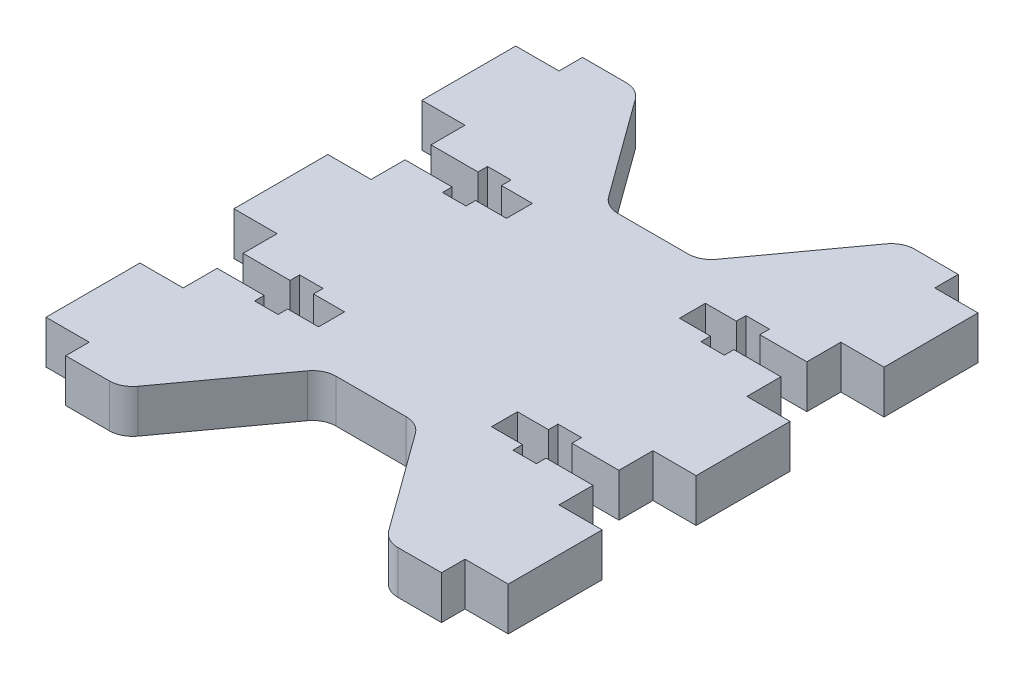
SolidWorks part; units mm, degrees
ref_plane "Front Plane" through (0, 0, 0) normal (0, 0, 1) x (1, 0, 0)
ref_plane "Top Plane" through (0, 0, 0) normal (0, 1, 0) x (1, 0, 0)
ref_plane "Right Plane" through (0, 0, 0) normal (1, 0, 0) x (0, 0, -1)
sketch "Sketch1" plane through (0, 0, 0) normal (0, 1, 0) x (1, 0, 0)
  line L0 (0, 34.925) -> (0, -34.925) construction
  line L1 (25.4, -34.925) -> (17.8955, -34.925)
  line L2 (25.4, -34.925) -> (25.4, -31.75)
  line L3 (25.4, 34.925) -> (17.8955, 34.925)
  line L4 (-25.4, -34.925) -> (-25.4, -31.75)
  line L5 (25.4, -34.925) -> (-25.4, 34.925) construction
  line L6 (25.4, 34.925) -> (-25.4, -34.925) construction
  line L7 (-31.242, 19.05) -> (-25.4, 19.05)
  line L8 (-31.242, 19.05) -> (-31.242, 31.75)
  line L9 (-31.242, 31.75) -> (-25.4, 31.75)
  line L10 (-25.4, 6.35) -> (-25.4, 10.9474)
  line L11 (-31.242, 19.05) -> (-25.4, 31.75) construction
  line L12 (-31.242, 31.75) -> (-25.4, 19.05) construction
  line L13 (-31.242, -6.35) -> (-25.4, -6.35)
  line L14 (-31.242, -6.35) -> (-31.242, 6.35)
  line L15 (-31.242, 6.35) -> (-25.4, 6.35)
  line L16 (-25.4, -19.05) -> (-25.4, -14.4526)
  line L17 (-31.242, -6.35) -> (-25.4, 6.35) construction
  line L18 (-31.242, 6.35) -> (-25.4, -6.35) construction
  line L19 (-31.242, -31.75) -> (-25.4, -31.75)
  line L20 (-31.242, -31.75) -> (-31.242, -19.05)
  line L21 (-31.242, -19.05) -> (-25.4, -19.05)
  line L22 (-25.4, 12.7) -> (25.4, 12.7) construction
  line L23 (-31.242, -31.75) -> (-25.4, -19.05) construction
  line L24 (-31.242, -19.05) -> (-25.4, -31.75) construction
  line L25 (-25.4, 31.75) -> (-25.4, 34.925)
  line L26 (-25.4, 0) -> (25.4, 0) construction
  line L27 (-19.05, 14.4526) -> (-19.05, 15.748)
  line L28 (-19.05, 10.9474) -> (-25.4, 10.9474)
  line L29 (-15.875, 14.4526) -> (-15.875, 15.748)
  line L30 (-19.05, 14.4526) -> (-25.4, 14.4526)
  line L31 (-11.692, -14.4526) -> (-15.875, -10.9474) construction
  line L32 (-19.05, 10.9474) -> (-25.4, 14.4526) construction
  line L33 (-19.05, 14.4526) -> (-25.4, 10.9474) construction
  line L34 (-15.875, 9.652) -> (-19.05, 9.652)
  line L35 (-15.875, 9.652) -> (-15.875, 10.9474)
  line L36 (-15.875, 15.748) -> (-19.05, 15.748)
  line L37 (-19.05, 9.652) -> (-19.05, 10.9474)
  line L38 (-15.875, 9.652) -> (-19.05, 15.748) construction
  line L39 (-15.875, 15.748) -> (-19.05, 9.652) construction
  line L40 (-11.692, 10.9474) -> (-15.875, 10.9474)
  line L41 (-11.692, 10.9474) -> (-11.692, 14.4526)
  line L42 (-11.692, 14.4526) -> (-15.875, 14.4526)
  line L43 (-25.4, 14.4526) -> (-25.4, 19.05)
  line L44 (-11.692, 10.9474) -> (-15.875, 14.4526) construction
  line L45 (-11.692, 14.4526) -> (-15.875, 10.9474) construction
  line L46 (-11.692, -10.9474) -> (-15.875, -14.4526) construction
  line L47 (-15.875, -15.748) -> (-19.05, -9.652) construction
  line L48 (-15.875, -9.652) -> (-19.05, -15.748) construction
  line L49 (-19.05, -14.4526) -> (-25.4, -10.9474) construction
  line L50 (-19.05, -10.9474) -> (-25.4, -14.4526) construction
  line L51 (-11.692, -14.4526) -> (-15.875, -14.4526)
  line L52 (-11.692, -10.9474) -> (-11.692, -14.4526)
  line L53 (-11.692, -10.9474) -> (-15.875, -10.9474)
  line L54 (-19.05, -9.652) -> (-19.05, -10.9474)
  line L55 (-15.875, -15.748) -> (-19.05, -15.748)
  line L56 (-15.875, -9.652) -> (-15.875, -10.9474)
  line L57 (-15.875, -9.652) -> (-19.05, -9.652)
  line L58 (-19.05, -14.4526) -> (-25.4, -14.4526)
  line L59 (-15.875, -14.4526) -> (-15.875, -15.748)
  line L60 (-19.05, -10.9474) -> (-25.4, -10.9474)
  line L61 (-19.05, -14.4526) -> (-19.05, -15.748)
  line L62 (-25.4, -10.9474) -> (-25.4, -6.35)
  line L63 (19.05, -10.9474) -> (25.4, -14.4526) construction
  line L64 (19.05, -14.4526) -> (25.4, -10.9474) construction
  line L65 (15.875, -9.652) -> (19.05, -15.748) construction
  line L66 (15.875, -15.748) -> (19.05, -9.652) construction
  line L67 (11.692, -10.9474) -> (15.875, -14.4526) construction
  line L68 (11.692, 14.4526) -> (15.875, 10.9474) construction
  line L69 (11.692, 10.9474) -> (15.875, 14.4526) construction
  line L70 (15.875, 15.748) -> (19.05, 9.652) construction
  line L71 (15.875, 9.652) -> (19.05, 15.748) construction
  line L72 (19.05, 14.4526) -> (25.4, 10.9474) construction
  line L73 (19.05, 10.9474) -> (25.4, 14.4526) construction
  line L74 (11.692, -14.4526) -> (15.875, -10.9474) construction
  line L75 (31.242, -19.05) -> (25.4, -31.75) construction
  line L76 (31.242, -31.75) -> (25.4, -19.05) construction
  line L77 (31.242, 6.35) -> (25.4, -6.35) construction
  line L78 (31.242, -6.35) -> (25.4, 6.35) construction
  line L79 (31.242, 31.75) -> (25.4, 19.05) construction
  line L80 (31.242, 19.05) -> (25.4, 31.75) construction
  line L81 (25.4, -10.9474) -> (25.4, -6.35)
  line L82 (19.05, -14.4526) -> (19.05, -15.748)
  line L83 (19.05, -10.9474) -> (25.4, -10.9474)
  line L84 (15.875, -14.4526) -> (15.875, -15.748)
  line L85 (19.05, -14.4526) -> (25.4, -14.4526)
  line L86 (15.875, -9.652) -> (19.05, -9.652)
  line L87 (15.875, -9.652) -> (15.875, -10.9474)
  line L88 (15.875, -15.748) -> (19.05, -15.748)
  line L89 (19.05, -9.652) -> (19.05, -10.9474)
  line L90 (11.692, -10.9474) -> (15.875, -10.9474)
  line L91 (11.692, -10.9474) -> (11.692, -14.4526)
  line L92 (11.692, -14.4526) -> (15.875, -14.4526)
  line L93 (25.4, 14.4526) -> (25.4, 19.05)
  line L94 (11.692, 14.4526) -> (15.875, 14.4526)
  line L95 (11.692, 10.9474) -> (11.692, 14.4526)
  line L96 (11.692, 10.9474) -> (15.875, 10.9474)
  line L97 (19.05, 9.652) -> (19.05, 10.9474)
  line L98 (15.875, 15.748) -> (19.05, 15.748)
  line L99 (15.875, 9.652) -> (15.875, 10.9474)
  line L100 (15.875, 9.652) -> (19.05, 9.652)
  line L101 (19.05, 14.4526) -> (25.4, 14.4526)
  line L102 (15.875, 14.4526) -> (15.875, 15.748)
  line L103 (19.05, 10.9474) -> (25.4, 10.9474)
  line L104 (19.05, 14.4526) -> (19.05, 15.748)
  line L105 (25.4, 31.75) -> (25.4, 34.925)
  line L106 (31.242, -19.05) -> (25.4, -19.05)
  line L107 (31.242, -31.75) -> (31.242, -19.05)
  line L108 (31.242, -31.75) -> (25.4, -31.75)
  line L109 (25.4, -19.05) -> (25.4, -14.4526)
  line L110 (31.242, 6.35) -> (25.4, 6.35)
  line L111 (31.242, -6.35) -> (31.242, 6.35)
  line L112 (31.242, -6.35) -> (25.4, -6.35)
  line L113 (25.4, 6.35) -> (25.4, 10.9474)
  line L114 (31.242, 31.75) -> (25.4, 31.75)
  line L115 (31.242, 19.05) -> (31.242, 31.75)
  line L116 (31.242, 19.05) -> (25.4, 19.05)
  line L117 (6.35, 19.05) -> (-6.35, 19.05)
  line L118 (-6.35, 19.05) -> (-17.8955, 34.925)
  line L119 (6.35, 19.05) -> (17.8955, 34.925)
  line L120 (-6.35, -19.05) -> (-17.8955, -34.925)
  line L121 (6.35, -19.05) -> (-6.35, -19.05)
  line L122 (6.35, -19.05) -> (17.8955, -34.925)
  line L123 (-17.8955, -34.925) -> (-25.4, -34.925)
  line L124 (-17.8955, 34.925) -> (-25.4, 34.925)
  point P0 (0, 0)
  point P6 (-28.321, 25.4)
  point P14 (-28.321, 0)
  point P19 (-28.321, -25.4)
  point P27 (-22.225, 12.7)
  point P32 (-17.4625, 12.7)
  point P37 (-13.7835, 12.7)
  point P54 (-13.7835, -12.7)
  point P55 (-17.4625, -12.7)
  point P56 (-22.225, -12.7)
  point P93 (22.225, -12.7)
  point P94 (17.4625, -12.7)
  point P95 (13.7835, -12.7)
  point P96 (13.7835, 12.7)
  point P97 (17.4625, 12.7)
  point P98 (22.225, 12.7)
  point P99 (28.321, -25.4)
  point P100 (28.321, 0)
  point P101 (28.321, 25.4)
  point P105 (0, 19.05)
  dimension "D1" = 50.8
  dimension "D2" = 69.85
  dimension "D3" = 5.842
  dimension "D4" = 12.7
  dimension "D5" = 9.525
  dimension "D7" = 3.5052
  dimension "D8" = 3.5052
  dimension "D9" = 6.35
  dimension "D10" = 6.096
  dimension "D11" = 3.175
  dimension "D12" = 4.183
  dimension "D13" = 19.05
  dimension "D14" = 25.4
  dimension "D15" = 12.7
  dimension "D6" = 3
extrude "Boss-Extrude1" add sketch "Sketch1" along normal blind 5.842
fillet "Fillet1" radius 3.175 8 edges at (17.8955, 2.921, -34.925) (6.35, 2.921, -19.05) (-6.35, 2.921, -19.05) (-17.8955, 2.921, -34.925) (17.8955, 2.921, 34.925) (6.35, 2.921, 19.05) (-6.35, 2.921, 19.05) (-17.8955, 2.921, 34.925)
